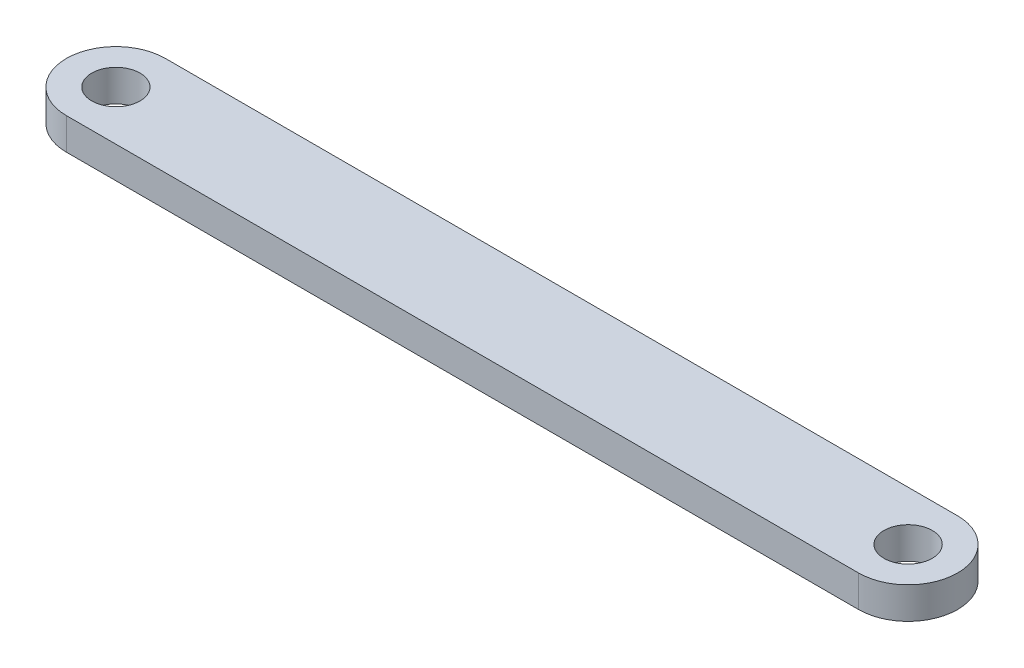
SolidWorks part; units mm, degrees
ref_plane "前视基准面" through (0, 0, 0) normal (0, 0, 1) x (1, 0, 0)
ref_plane "上视基准面" through (0, 0, 0) normal (0, 1, 0) x (1, 0, 0)
ref_plane "右视基准面" through (0, 0, 0) normal (1, 0, 0) x (0, 0, -1)
sketch "草图1" plane through (0, 0, 0) normal (0, 1, 0) x (1, 0, 0)
  line L0 (0, 0) -> (200, 0) construction
  line L1 (0, 12.5) -> (200, 12.5)
  line L2 (0, -12.5) -> (200, -12.5)
  arc A0 (0, 12.5) -> (0, -12.5) centre (0, 0) ccw
  arc A1 (200, -12.5) -> (200, 12.5) centre (200, 0) ccw
  circle A2 centre (0, 0) radius 6.1
  circle A3 centre (200, 0) radius 6.1
  point P3 (100, 0)
  dimension "D2" = 12.2
  dimension "D4" = 12.2
  dimension "D1" = 200
  dimension "D3" = 25
extrude "凸台-拉伸1" add sketch "草图1" along normal blind 8
